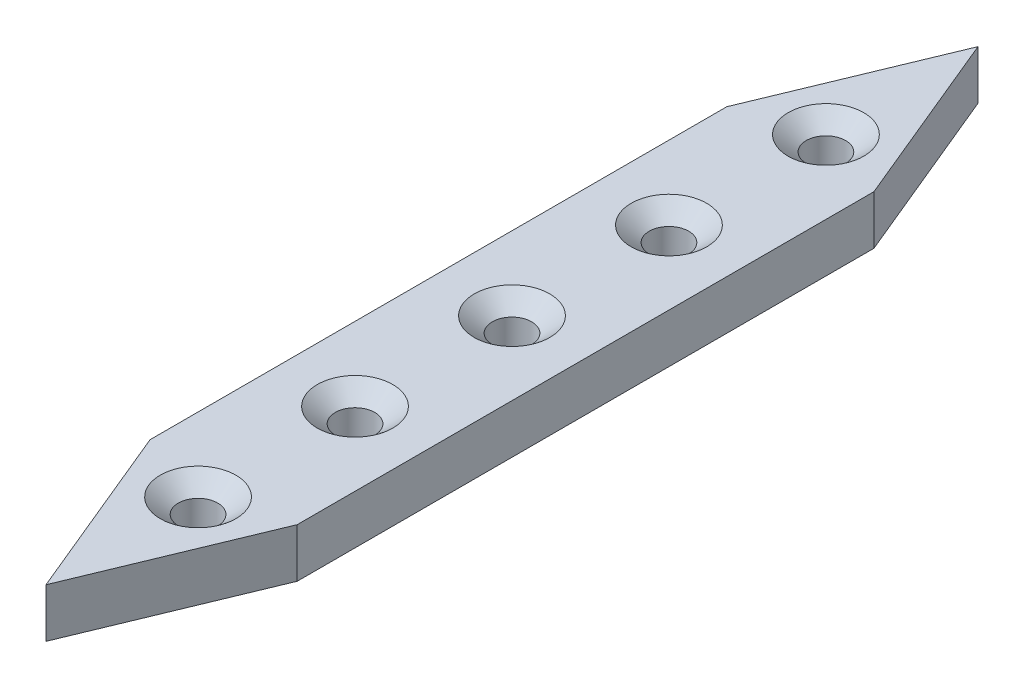
SolidWorks part; units mm, degrees
material "PE Low/Medium Density"
ref_plane "Front Plane" through (0, 0, 0) normal (0, 0, 1) x (1, 0, 0)
ref_plane "Top Plane" through (0, 0, 0) normal (0, 1, 0) x (1, 0, 0)
ref_plane "Right Plane" through (0, 0, 0) normal (1, 0, 0) x (0, 0, -1)
sketch "Sketch1" plane through (0, 0, 0) normal (0, 1, 0) x (1, 0, 0)
  line L0 (0, 60.325) -> (0, -48.1572) construction
  line L1 (0, 60.325) -> (-9.525, 37.3296)
  line L2 (-9.525, 37.3296) -> (-9.525, -37.3296)
  line L3 (-28.5797, 0) -> (23.9031, 0) construction
  line L4 (0, -60.325) -> (-9.525, -37.3296)
  line L5 (0, -60.325) -> (9.525, -37.3296)
  line L6 (9.525, 37.3296) -> (9.525, -37.3296)
  line L7 (0, 60.325) -> (9.525, 37.3296)
  point P9 (-9.525, 0)
  point P10 (9.525, 0)
  dimension "D1" = 19.05
  dimension "D2" = 120.65
  dimension "D3" = 22.5
extrude "Boss-Extrude1" add sketch "Sketch1" along normal blind 6.35
hole_wizard "CSK for #10 Flat Head Machine Screw (100)1" positions "Sketch4" profile "Sketch5" countersink size "#10" standard "ANSI Inch" end condition through all
sketch "Sketch4" plane through (0, 6.35, 0) normal (0, 1, 0) x (1, 0, 0)
  line L0 (-9.525, 0) -> (9.525, 0) construction
  line L1 (-9.525, 37.3296) -> (-9.525, -37.3296) construction
  line L2 (9.525, -37.3296) -> (9.525, 37.3296) construction
  point P0 (0, 20.32)
  point P2 (0, 40.64)
  point P14 (0, 0)
  point P16 (0, -20.32)
  point P18 (0, -40.64)
  dimension "D1" = 20.32
  dimension "D2" = 40.64
  dimension "D3" = 20.32
  dimension "D4" = 40.64
sketch "Sketch5" plane through (0, 6.35, -20.32) normal (1, 0, 0) x (0, 0, 1)
  line L0 (0, 0) -> (0, 6.35)
  line L1 (0, 6.35) -> (2.5527, 6.35)
  line L2 (2.5527, 6.35) -> (2.5527, 1.9608)
  line L3 (2.5527, 1.9608) -> (4.8895, 0)
  line L5 (4.8895, 0) -> (0, 0)
  line L6 (-2.5527, 1.9608) -> (-4.8895, 0) construction
  line L11 (0, -6.35) -> (0, 107.95) construction
  dimension "Thru Hole Dia." = 5.1054
  dimension "Thru Hole Depth" = 6.35
  dimension "Near C'Sink Dia." = 9.779
  dimension "Near C'Sink Angle" = 100
